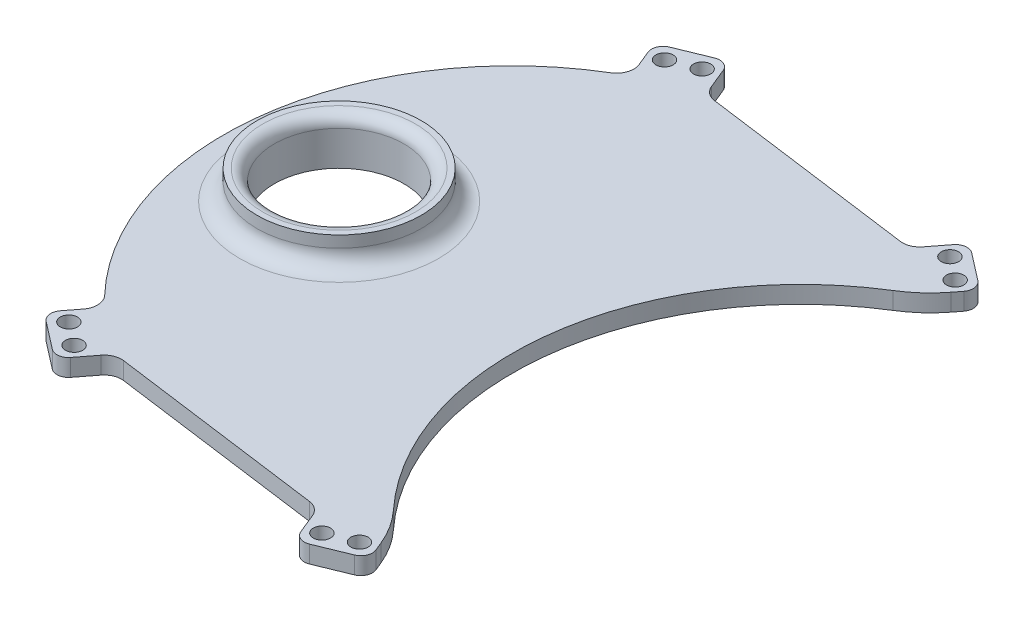
SolidWorks part; units mm, degrees
ref_plane "Front" through (0, 0, 0) normal (0, 0, 1) x (1, 0, 0)
ref_plane "Top" through (0, 0, 0) normal (0, 1, 0) x (1, 0, 0)
ref_plane "Right" through (0, 0, 0) normal (1, 0, 0) x (0, 0, -1)
sketch "Sketch1" plane through (0, 0, 0) normal (0, 1, 0) x (1, 0, 0)
  line L0 (-34.3716, -36.3125) -> (-38.9568, -42.2476)
  line L1 (-38.9568, -42.2476) -> (-31.0432, -48.3612)
  line L2 (-31.0432, -48.3612) -> (-26.458, -42.4261)
  line L3 (14.2617, -47.9229) -> (17.1091, -54.8614)
  line L4 (17.1091, -54.8614) -> (26.3604, -51.0648)
  line L5 (26.3604, -51.0648) -> (23.513, -44.1264)
  line L6 (34.3716, 36.3125) -> (38.9568, 42.2476)
  line L7 (38.9568, 42.2476) -> (31.0432, 48.3612)
  line L8 (31.0432, 48.3612) -> (26.458, 42.4261)
  line L9 (-14.2617, 47.9229) -> (-17.1091, 54.8614)
  line L10 (-17.1091, 54.8614) -> (-26.3604, 51.0648)
  line L11 (-26.3604, 51.0648) -> (-23.513, 44.1264)
  circle A0 centre (0, 0) radius 50 construction
  arc A1 (-34.3716, -36.3125) -> (-26.458, -42.4261) centre (0, 0) ccw
  arc A2 (14.2617, -47.9229) -> (23.513, -44.1264) centre (0, 0) ccw
  arc A3 (34.3716, 36.3125) -> (26.458, 42.4261) centre (0, 0) ccw
  arc A4 (-14.2617, 47.9229) -> (-23.513, 44.1264) centre (0, 0) ccw
  point P5 (-35, -45.3044)
  point P15 (0, 0)
  point P20 (0, 0)
  point P25 (0, 0)
  dimension "D1" = 100
  dimension "D2" = 7.5
  dimension "D3" = 10
  dimension "D4" = 35
  dimension "D6" = 60
  dimension "D8" = 180
  dimension "D10" = 120
  dimension "D5" = 2
  dimension "D7" = 2
  dimension "D9" = 2
extrude "Boss-Extrude1" add sketch "Sketch1" along normal blind 3
sketch "Sketch2" plane through (0, 3, 0) normal (0, 1, 0) x (1, 0, 0)
  line L2 (-26.458, -42.4261) -> (14.2617, -47.9229)
  line L4 (26.458, 42.4261) -> (-14.2617, 47.9229)
  arc A0 (-23.513, 44.1264) -> (-34.3716, -36.3125) centre (0, 0) ccw
  arc A1 (34.3716, 36.3125) -> (23.513, -44.1264) centre (57.8846, -7.8139) ccw
  arc A2 (14.2617, -47.9229) -> (23.513, -44.1264) centre (0, 0) ccw
  arc A3 (14.2617, -47.9229) -> (23.513, -44.1264) centre (0, 0) ccw
  arc A5 (-34.3716, -36.3125) -> (-26.458, -42.4261) centre (0, 0) ccw
  arc A6 (-34.3716, -36.3125) -> (-26.458, -42.4261) centre (0, 0) ccw
  arc A8 (-14.2617, 47.9229) -> (-23.513, 44.1264) centre (0, 0) ccw
  arc A9 (-14.2617, 47.9229) -> (-23.513, 44.1264) centre (0, 0) ccw
  circle A10 centre (-30, 0) radius 11.25
  arc A11 (34.3716, 36.3125) -> (26.458, 42.4261) centre (0, 0) ccw
  arc A12 (34.3716, 36.3125) -> (26.458, 42.4261) centre (0, 0) ccw
  dimension "D5" = 22.5
  dimension "D7" = 50
  dimension "D8" = 50
  dimension "D6" = 30
  dimension "D1" = 0
  dimension "D2" = 0
  dimension "D3" = 0
  dimension "D4" = 0
extrude "Boss-Extrude2" add sketch "Sketch2" against normal up to surface (3 mm away) up to face at (-32.7457, 0, 42.3864)
sketch "Sketch3" plane through (0, 3, 0) normal (0, 1, 0) x (1, 0, 0)
  line L0 (-33.3188, -43.1282) -> (-37.2755, -40.0714) construction
  line L1 (-31.0432, -48.3612) -> (-26.458, -42.4261) construction
  line L2 (-34.3716, -36.3125) -> (-38.9568, -42.2476) construction
  line L3 (-35, -45.3044) -> (-33.3188, -43.1282) construction
  line L4 (-38.9568, -42.2476) -> (-31.0432, -48.3612) construction
  circle A0 centre (-35.2971, -41.5998) radius 1.5
  circle A1 centre (-31.3404, -44.6566) radius 1.5
  point P0 (-31.7515, -44.6549)
  point P12 (-35.2971, -41.5998)
  dimension "D1" = 3
  dimension "D2" = 2.75
extrude "Cut-Extrude1" cut sketch "Sketch3" against normal up to next
fillet "Fillet1" radius 2 2 edges at (-31.0432, 1.5, 48.3612) (-38.9568, 1.5, 42.2476)
sketch "Sketch4" plane through (0, 3, 0) normal (0, 1, 0) x (1, 0, 0)
  circle A1 centre (-30, 0) radius 14.25
  circle A2 centre (-30, 0) radius 11.25
  circle A3 centre (-30, 0) radius 11.25
  dimension "D1" = 0
  dimension "D2" = 3
extrude "Boss-Extrude3" add sketch "Sketch4" along normal blind 5
fillet "Fillet3" radius 2 1 edges at (-30, 8, 11.25)
fillet "Fillet2" radius 3 1 edges at (-30, 3, 14.25)
sketch "Sketch6" plane through (0, 3, 0) normal (0, 1, 0) x (1, 0, 0)
  line L0 (16.0651, -52.3172) -> (20.6907, -50.419) construction
  line L1 (14.2617, -47.9229) -> (17.1091, -54.8614) construction
  line L2 (20.6907, -50.419) -> (21.7348, -52.9631) construction
  line L3 (17.1091, -54.8614) -> (26.3604, -51.0648) construction
  line L4 (26.3604, -51.0648) -> (23.513, -44.1264) construction
  circle A0 centre (18.3779, -51.3681) radius 1.5
  circle A1 centre (23.0036, -49.4699) radius 1.5
  point P4 (0, 0)
  point P8 (18.3779, -51.3681)
  dimension "D2" = 3
  dimension "D1" = 2.75
extrude "Cut-Extrude2" cut sketch "Sketch6" against normal up to next
fillet "Fillet4" radius 2 2 edges at (26.3604, 1.5, 51.0648) (17.1091, 1.5, 54.8614)
sketch "Sketch7" plane through (0, 3, 0) normal (0, 1, 0) x (1, 0, 0)
  line L0 (-16.0651, 52.3172) -> (-20.6907, 50.419) construction
  line L1 (-14.2617, 47.9229) -> (-17.1091, 54.8614) construction
  line L2 (-20.6907, 50.419) -> (-21.7348, 52.9631) construction
  line L3 (-17.1091, 54.8614) -> (-26.3604, 51.0648) construction
  line L4 (-26.3604, 51.0648) -> (-23.513, 44.1264) construction
  circle A0 centre (-18.3779, 51.3681) radius 1.5
  circle A1 centre (-23.0036, 49.4699) radius 1.5
  point P11 (0, 0)
  point P12 (-17.956, 51.5413)
  point P13 (-18.3779, 51.3681)
  dimension "D2" = 3
  dimension "D1" = 2.75
extrude "Cut-Extrude3" cut sketch "Sketch7" against normal up to next
fillet "Fillet5" radius 2 2 edges at (-26.3604, 1.5, -51.0648) (-17.1091, 1.5, -54.8614)
sketch "Sketch8" plane through (0, 3, 0) normal (0, 1, 0) x (1, 0, 0)
  line L0 (37.2755, 40.0714) -> (33.3188, 43.1282) construction
  line L1 (34.3716, 36.3125) -> (38.9568, 42.2476) construction
  line L2 (33.3188, 43.1282) -> (35, 45.3044) construction
  line L3 (38.9568, 42.2476) -> (31.0432, 48.3612) construction
  circle A0 centre (35.2971, 41.5998) radius 1.5
  circle A1 centre (31.3404, 44.6566) radius 1.5
  point P9 (0, 0)
  point P10 (35.2971, 41.5998)
  point P11 (0, 0)
  dimension "D2" = 3
  dimension "D1" = 2.75
extrude "Cut-Extrude4" cut sketch "Sketch8" against normal up to next
fillet "Fillet6" radius 2 2 edges at (38.9568, 1.5, -42.2476) (31.0432, 1.5, -48.3612)
fillet "Fillet7" radius 3 6 edges at (-23.513, 1.5, -44.1264) (-14.2617, 1.5, -47.9229) (26.458, 1.5, -42.4261) (14.2617, 1.5, 47.9229) (-26.458, 1.5, 42.4261) (-34.3716, 1.5, 36.3125)
fillet "Fillet8" radius 20 2 edges at (34.3716, 1.5, -36.3125) (23.513, 1.5, 44.1264)
